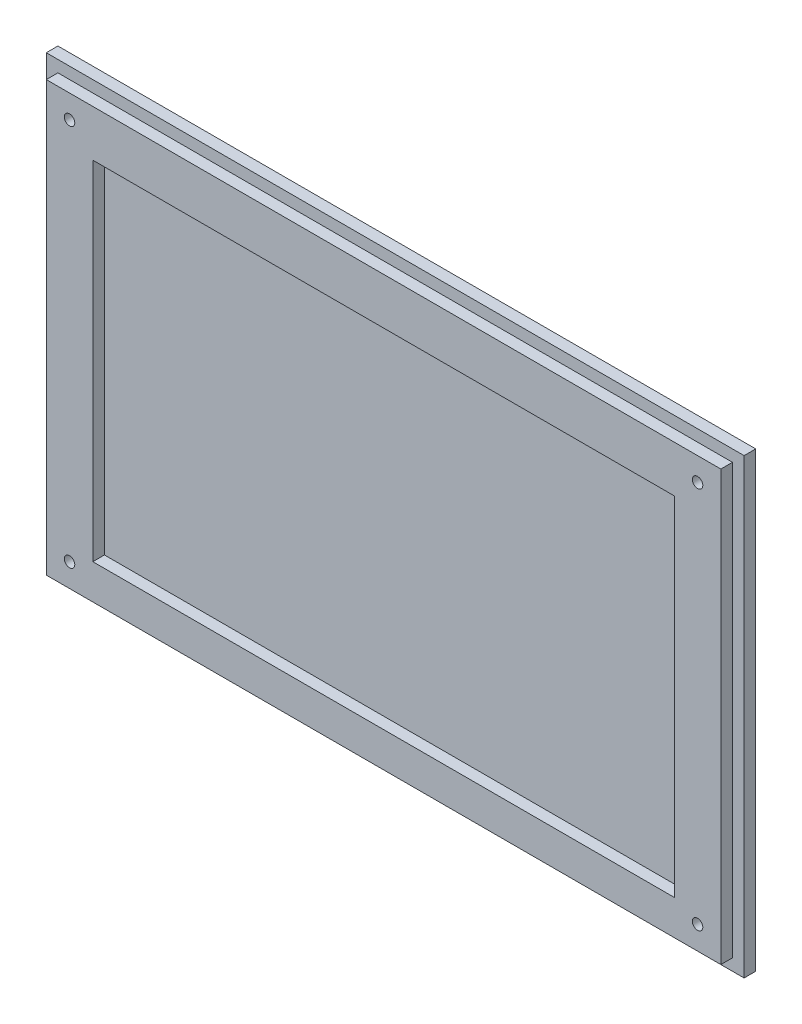
SolidWorks part; units mm, degrees
ref_plane "Ebene vorne" through (0, 0, 0) normal (0, 0, 1) x (1, 0, 0)
ref_plane "Ebene oben" through (0, 0, 0) normal (0, 1, 0) x (1, 0, 0)
ref_plane "Ebene rechts" through (0, 0, 0) normal (1, 0, 0) x (0, 0, -1)
sketch "Skizze1" plane through (0, 0, 0) normal (0, 0, 1) x (1, 0, 0)
  line L0 (-130.2667, -95.4528) -> (169.7333, -95.4528)
  line L1 (-130.2667, -95.4528) -> (-130.2667, 99.0472)
  line L2 (-130.2667, 99.0472) -> (169.7333, 99.0472)
  line L3 (169.7333, -95.4528) -> (169.7333, 99.0472)
  line L4 (-130.2667, -95.4528) -> (169.7333, 99.0472) construction
  line L5 (-130.2667, 99.0472) -> (169.7333, -95.4528) construction
  point P0 (19.7333, 1.7972)
  dimension "D1" = 194.5
  dimension "D2" = 300
extrude "Aufsatz-Linear austragen1" add sketch "Skizze1" along normal blind 5
sketch "Skizze2" plane through (0, 0, 5) normal (0, 0, 1) x (1, 0, 0)
  line L0 (-125.2667, 94.0472) -> (164.7333, 94.0472)
  line L1 (-125.2667, 94.0472) -> (-125.2667, -90.4528)
  line L2 (164.7333, 94.0472) -> (164.7333, -90.4528)
  line L3 (-125.2667, -90.4528) -> (164.7333, -90.4528)
  line L4 (144.7333, -75.4528) -> (-105.2667, -75.4528)
  line L5 (144.7333, -75.4528) -> (144.7333, 74.0472)
  line L6 (144.7333, 74.0472) -> (-105.2667, 74.0472)
  line L7 (-105.2667, -75.4528) -> (-105.2667, 74.0472)
  line L8 (144.7333, -75.4528) -> (-105.2667, 74.0472) construction
  line L9 (144.7333, 74.0472) -> (-105.2667, -75.4528) construction
  line L10 (-130.2667, 99.0472) -> (-130.2667, -95.4528) construction
  line L11 (169.7333, 99.0472) -> (-130.2667, 99.0472) construction
  line L12 (169.7333, -95.4528) -> (169.7333, 99.0472) construction
  line L13 (-130.2667, -95.4528) -> (169.7333, -95.4528) construction
  point P0 (19.7333, -0.7028)
  dimension "D1" = 20
  dimension "D2" = 20
  dimension "D3" = 5
  dimension "D4" = 5
  dimension "D5" = 5
  dimension "D6" = 5
  dimension "D7" = 20
  dimension "D8" = 20
extrude "Aufsatz-Linear austragen2" add sketch "Skizze2" along normal blind 5
sketch "Skizze4" plane through (0, 0, 0) normal (0, 0, -1) x (-1, 0, 0)
  line L0 (-144.7333, 74.0472) -> (105.2667, 74.0472) construction
  line L1 (-164.7333, 94.0472) -> (125.2667, 94.0472) construction
  line L2 (125.2667, 94.0472) -> (125.2667, -90.4528) construction
  circle A0 centre (115.2667, 84.0472) radius 10
hole_wizard "Stirnsenkung für M4 Senkschraube (Kopf Button)1" positions "Skizze6" profile "Skizze5" counterbore size "M4" standard "ANSI Metrisch" end condition through all
sketch "Skizze6" plane through (0, 0, 0) normal (0, 0, -1) x (-1, 0, 0)
  point P0 (115.2667, 84.0472)
sketch "Skizze5" plane through (-115.2667, 84.0472, 0) normal (1, 0, 0) x (0, 1, 0)
  line L0 (0, 0) -> (0, 10)
  line L1 (0, 10) -> (2.25, 10)
  line L3 (2.25, 10) -> (2.25, 2.2)
  line L4 (2.25, 2.2) -> (4.3, 2.2)
  line L5 (4.3, 2.2) -> (4.3, 0)
  line L7 (4.3, 0) -> (0, 0)
  line L11 (0, -6.35) -> (0, 107.95) construction
  dimension "Bohrerdurchmesser" = 4.5
  dimension "Bohrungstiefe" = 10
  dimension "Senkdurchmesser2" = 8.6
  dimension "Senktiefe2" = 2.2
ref_plane "Ebene1" through (0, 1.7972, 0) normal (0, 1, 0) x (1, 0, 0)
ref_plane "Ebene2" through (19.7333, 0, 0) normal (1, 0, 0) x (0, 0, -1)
mirror "Spiegeln1" about plane through (0, 1.7972, 0) normal (0, 1, 0) of "Stirnsenkung für M4 Senkschraube (Kopf Button)1"
mirror "Spiegeln2" about plane through (19.7333, 0, 0) normal (1, 0, 0) of "Spiegeln1", "Stirnsenkung für M4 Senkschraube (Kopf Button)1"
